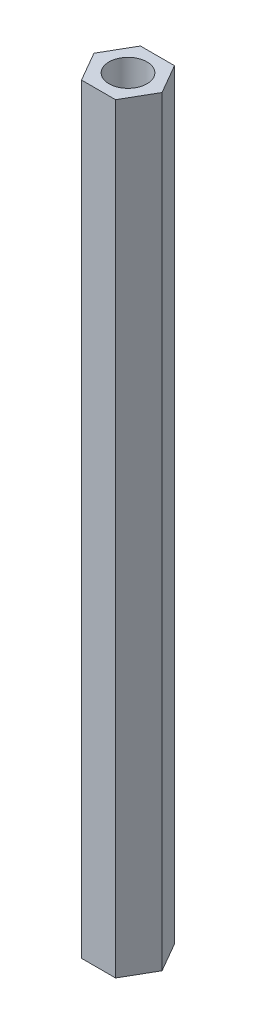
SolidWorks part; units mm, degrees
material "Настроенная пользователем пластмасса"
ref_plane "Спереди" through (0, 0, 0) normal (0, 0, 1) x (1, 0, 0)
ref_plane "Сверху" through (0, 0, 0) normal (0, 1, 0) x (1, 0, 0)
ref_plane "Справа" through (0, 0, 0) normal (1, 0, 0) x (0, 0, -1)
other "Configuration Table"
sketch "Эскиз1" plane through (0, 0, 0) normal (0, 1, 0) x (1, 0, 0)
  line L1 (2.6847, 0) -> (1.3423, 2.325)
  line L2 (1.3423, 2.325) -> (-1.3423, 2.325)
  line L3 (-1.3423, 2.325) -> (-2.6847, 0)
  line L4 (-2.6847, 0) -> (-1.3423, -2.325)
  line L5 (-1.3423, -2.325) -> (1.3423, -2.325)
  line L6 (1.3423, -2.325) -> (2.6847, 0)
  circle A0 centre (0, 0) radius 2.325 construction
  circle A1 centre (0, 0) radius 1.5
extrude "Бобышка-Вытянуть1" add sketch "Эскиз1" along normal blind 60
